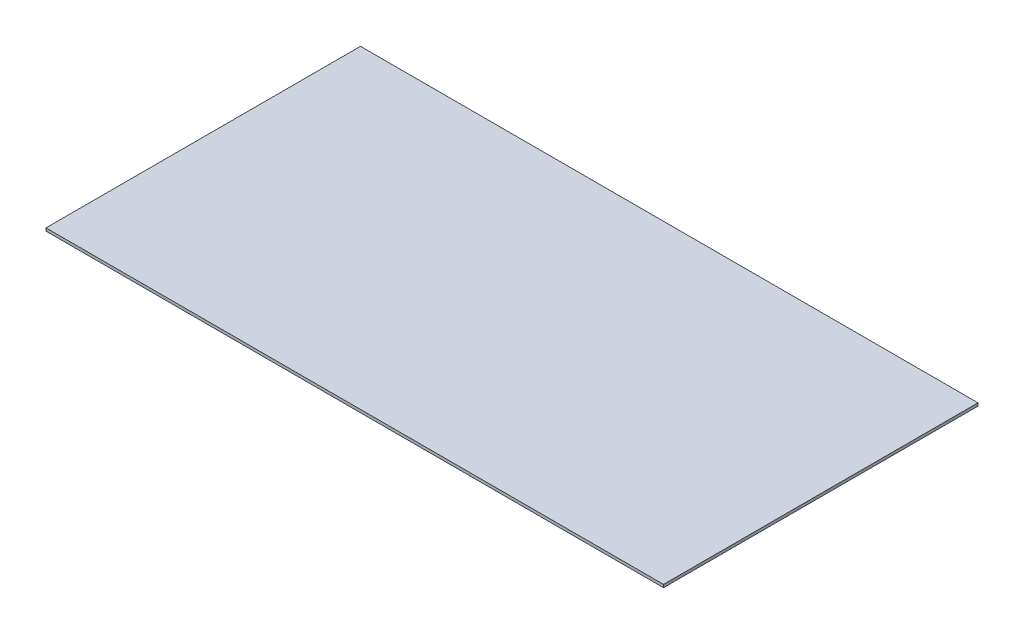
SolidWorks part; units mm, degrees
material "Acrylic (Medium-high impact)"
ref_plane "Front Plane" through (0, 0, 0) normal (0, 0, 1) x (1, 0, 0)
ref_plane "Top Plane" through (0, 0, 0) normal (0, 1, 0) x (1, 0, 0)
ref_plane "Right Plane" through (0, 0, 0) normal (1, 0, 0) x (0, 0, -1)
sketch "Sketch1" plane through (0, 0, 0) normal (0, 1, 0) x (1, 0, 0)
  line L1 (-158.0622, 57.222) -> (527.7378, 57.222)
  line L2 (-158.0622, 57.222) -> (-158.0622, -292.028)
  line L3 (-158.0622, -292.028) -> (527.7378, -292.028)
  line L4 (527.7378, 57.222) -> (527.7378, -292.028)
  dimension "D1" = 349.25
  dimension "D2" = 685.8
extrude "Boss-Extrude1" add sketch "Sketch1" along normal blind 3.175
